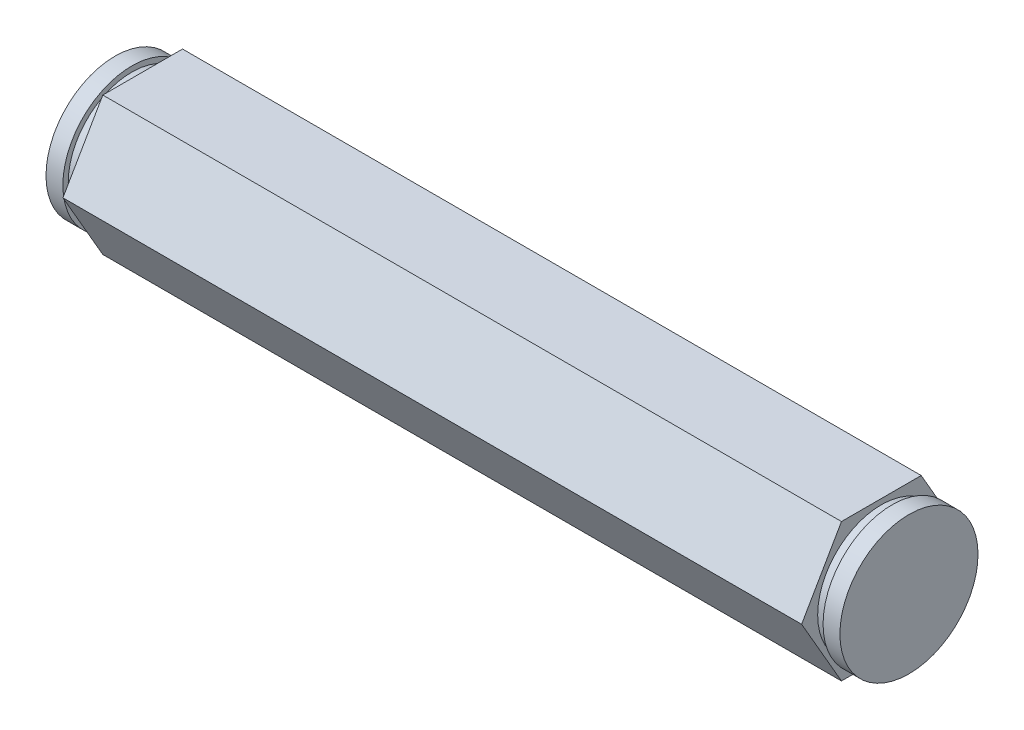
SolidWorks part; units mm, degrees
material "7075-T6 (SN)"
ref_plane "Front Plane" through (0, 0, 0) normal (0, 0, 1) x (1, 0, 0)
ref_plane "Top Plane" through (0, 0, 0) normal (0, 1, 0) x (1, 0, 0)
ref_plane "Right Plane" through (0, 0, 0) normal (1, 0, 0) x (0, 0, -1)
sketch "Sketch1" plane through (0, 0, 0) normal (1, 0, 0) x (0, 0, -1)
  line L1 (7.3323, 0) -> (3.6662, 6.35)
  line L2 (3.6662, 6.35) -> (-3.6662, 6.35)
  line L3 (-3.6662, 6.35) -> (-7.3323, 0)
  line L4 (-7.3323, 0) -> (-3.6662, -6.35)
  line L5 (-3.6662, -6.35) -> (3.6662, -6.35)
  line L6 (3.6662, -6.35) -> (7.3323, 0)
  circle A0 centre (0, 0) radius 6.35 construction
  dimension "D1" = 12.7
extrude "Boss-Extrude1" add sketch "Sketch1" along normal mid plane 73.015
sketch "Sketch2" plane through (0, 0, 0) normal (0, 1, 0) x (1, 0, 0)
  line L0 (33.9675, -5.8547) -> (34.9581, -5.8547)
  line L1 (34.9581, -5.8547) -> (34.9581, -6.35)
  line L2 (34.9581, -6.35) -> (36.5075, -6.35)
  line L3 (36.5075, -6.35) -> (36.5075, -8.89)
  line L4 (36.5075, -8.89) -> (33.9675, -8.89)
  line L5 (33.9675, -8.89) -> (33.9675, -5.8547)
  line L6 (0, 0) -> (49.5443, 0) construction
  dimension "D1" = 2.54
  dimension "D2" = 6.35
  dimension "D3" = 5.8547
  dimension "D4" = 2.54
  dimension "D5" = 0.9906
revolve "Cut-Revolve1" cut sketch "Sketch2" angle 360 about L6
mirror "Mirror1" about plane through (0, 0, 0) normal (1, 0, 0) of "Cut-Revolve1"
